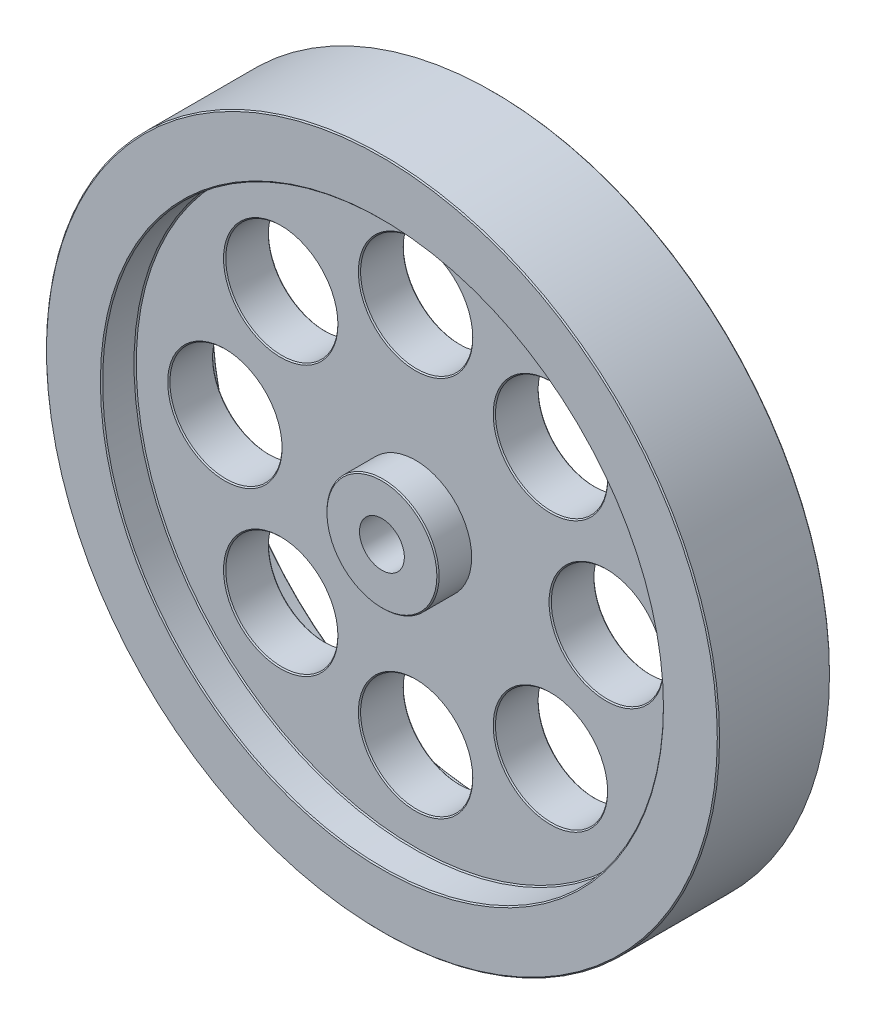
SolidWorks part; units mm, degrees
ref_plane "Front Plane" through (0, 0, 0) normal (0, 0, 1) x (1, 0, 0)
ref_plane "Top Plane" through (0, 0, 0) normal (0, 1, 0) x (1, 0, 0)
ref_plane "Right Plane" through (0, 0, 0) normal (1, 0, 0) x (0, 0, -1)
sketch "Sketch2" plane through (0, 0, 0) normal (0, 0, 1) x (1, 0, 0)
  circle A0 centre (0, 0) radius 30
  dimension "D1" = 60
extrude "Boss-Extrude2" add sketch "Sketch2" along normal mid plane 10
sketch "Sketch3" plane through (0, 0, 5) normal (0, 0, 1) x (1, 0, 0)
  circle A0 centre (0, 0) radius 25
  circle A1 centre (0, 0) radius 5
  dimension "D1" = 50
  dimension "D2" = 10
extrude "Cut-Extrude1" cut sketch "Sketch3" against normal blind 3
mirror "Mirror1" about plane through (0, 0, 0) normal (0, 0, 1) of "Cut-Extrude1"
sketch "Sketch4" plane through (0, 0, 2) normal (0, 0, 1) x (1, 0, 0)
  circle A0 centre (0, 0) radius 17 construction
  circle A1 centre (0, 17) radius 5
  circle A2 centre (12.0208, 12.0208) radius 5
  circle A3 centre (17, 0) radius 5
  circle A4 centre (12.0208, -12.0208) radius 5
  circle A5 centre (0, -17) radius 5
  circle A6 centre (-12.0208, -12.0208) radius 5
  circle A7 centre (-17, 0) radius 5
  circle A8 centre (-12.0208, 12.0208) radius 5
  point P22 (0, 0)
  dimension "D1" = 34
  dimension "D2" = 10
  dimension "D3" = 8
extrude "Cut-Extrude2" cut sketch "Sketch4" against normal through all
chamfer "Chamfer1" distance 0.1 angle 45 24 edges at (5, 0, -5) (17.0208, 12.0208, 2) (7.0208, 12.0208, -2) (22, 0, 2) (12, 0, -2) (17.0208, -12.0208, 2) (7.0208, -12.0208, -2) (5, -17, 2) (-5, -17, -2) (-7.0208, -12.0208, 2) (-17.0208, -12.0208, -2) (-12, 0, 2) (-22, 0, -2) (-7.0208, 12.0208, 2) (-17.0208, 12.0208, -2) (5, 17, 2) (-5, 17, -2) (30, 0, -5) (30, 0, 5) (25, 0, -2) (25, 0, -5) (25, 0, 2) (5, 0, 5) (25, 0, 5)
sketch "Sketch8" plane through (0, 0, 0) normal (1, 0, 0) x (0, 0, -1)
  line L0 (-5, 0) -> (-5, 2)
  line L1 (-5, 29.9) -> (-5, -29.9) construction
  line L2 (-5, 2) -> (1, 2)
  line L3 (1, 2) -> (1, 1.5)
  line L4 (1, 1.5) -> (3.5, 1.5)
  line L5 (3.5, 1.5) -> (5, 3)
  line L6 (5, -29.9) -> (5, 29.9) construction
  line L7 (5, 3) -> (5, 0)
  line L8 (5, 0) -> (-5, 0)
  dimension "D1" = 2
  dimension "D2" = 6
  dimension "D3" = 1.5
  dimension "D4" = 2.5
  dimension "D5" = 45
revolve "Cut-Revolve1" cut sketch "Sketch8" angle 360 about L8
